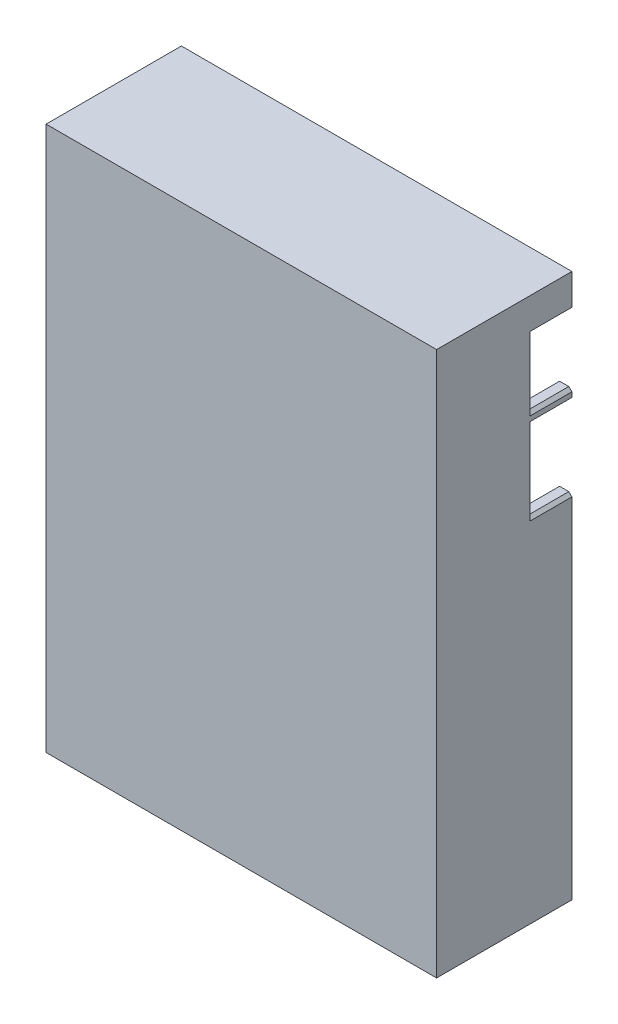
SolidWorks part; units mm, degrees
ref_plane "Front Plane" through (0, 0, 0) normal (0, 0, 1) x (1, 0, 0)
ref_plane "Top Plane" through (0, 0, 0) normal (0, 1, 0) x (1, 0, 0)
ref_plane "Right Plane" through (0, 0, 0) normal (1, 0, 0) x (0, 0, -1)
ref_plane "Plane1" through (0, 0, 2) normal (0, 0, 1) x (1, 0, 0)
sketch "Sketch2" plane through (0, 0, 2) normal (0, 0, 1) x (1, 0, 0)
  line L0 (-36.8212, -25.2032) -> (-36.8212, 57.2968) construction
  line L1 (-39.8212, 60.2968) -> (23.6788, 60.2968)
  line L2 (-39.8212, 60.2968) -> (-39.8212, -28.2032)
  line L3 (-39.8212, -28.2032) -> (23.6788, -28.2032)
  line L4 (23.6788, 60.2968) -> (23.6788, -28.2032)
  line L5 (-36.8212, 57.2968) -> (20.6788, 57.2968) construction
  line L6 (20.6788, 57.2968) -> (20.6788, -25.2032) construction
  line L7 (20.6788, -25.2032) -> (-36.8212, -25.2032) construction
  dimension "D1" = 3
  dimension "D2" = 3
  dimension "D3" = 3
  dimension "D4" = 3
extrude "Boss-Extrude1" add sketch "Sketch2" along normal blind 2
sketch "Sketch3" plane through (0, 0, 2) normal (0, 0, -1) x (-1, 0, 0)
  line L4 (39.8212, -28.2032) -> (39.8212, 60.2968)
  line L5 (39.8212, 60.2968) -> (-23.6788, 60.2968)
  line L6 (-23.6788, 60.2968) -> (-23.6788, -28.2032)
  line L7 (-23.6788, -28.2032) -> (39.8212, -28.2032)
  line L8 (39.8212, -28.2032) -> (39.8212, 60.2968)
  line L9 (39.8212, 60.2968) -> (-23.6788, 60.2968)
  line L10 (-23.6788, 60.2968) -> (-23.6788, -28.2032)
  line L11 (-23.6788, -28.2032) -> (39.8212, -28.2032)
  line L16 (37.8212, -26.2032) -> (37.8212, 58.2968)
  line L17 (37.8212, 58.2968) -> (-21.6788, 58.2968)
  line L18 (-21.6788, 58.2968) -> (-21.6788, -26.2032)
  line L19 (-21.6788, -26.2032) -> (37.8212, -26.2032)
  line L20 (37.8212, -26.2032) -> (37.8212, 58.2968)
  line L21 (37.8212, 58.2968) -> (-21.6788, 58.2968)
  line L22 (-21.6788, 58.2968) -> (-21.6788, -26.2032)
  line L23 (-21.6788, -26.2032) -> (37.8212, -26.2032)
  dimension "D1" = 0
  dimension "D2" = 2
extrude "Boss-Extrude2" add sketch "Sketch3" along normal blind 20
sketch "Sketch4" plane through (23.6788, 0, 0) normal (1, 0, 0) x (0, 0, -1)
  line L0 (18, 60.2968) -> (18, -28.2032) construction
  line L1 (18, 29.0468) -> (11.65, 29.0468)
  line L2 (18, 29.0468) -> (18, 42.0468)
  line L3 (18, 42.0468) -> (11.65, 42.0468)
  line L4 (11.65, 29.0468) -> (11.65, 42.0468)
  line L5 (11.65, -25.2032) -> (11.65, 57.2968) construction
  line L7 (18, 43.8468) -> (11.65, 43.8468)
  line L8 (18, 43.8468) -> (18, 54.7468)
  line L9 (18, 54.7468) -> (11.65, 54.7468)
  line L10 (11.65, 43.8468) -> (11.65, 54.7468)
  line L11 (16.95, 47.7968) -> (16.95, 50.7968) construction
  line L12 (16.95, 32.7968) -> (16.95, 38.2968) construction
  point P16 (16.95, 49.2968)
  point P17 (11.65, 49.2968)
  point P18 (16.95, 35.5468)
  point P19 (11.65, 35.5468)
  dimension "D1" = 10.9
  dimension "D2" = 13
extrude "Cut-Extrude1" cut sketch "Sketch4" against normal up to surface (2 mm away) up to face at (21.6788, 16.0468, -8)
chamfer "Chamfer1" distance 0.5 angle 45 6 edges at (23.6788, 54.7468, -14.825) (23.6788, 49.2968, -11.65) (23.6788, 43.8468, -14.825) (23.6788, 42.0468, -14.825) (23.6788, 35.5468, -11.65) (23.6788, 29.0468, -14.825)
sketch "Sketch5" plane through (-39.8212, 0, 0) normal (-1, 0, 0) x (0, 0, 1)
  line L0 (-18, -28.2032) -> (-18, 60.2968) construction
  line L1 (4, 60.2968) -> (-18, 60.2968) construction
  line L2 (-11.65, 57.2968) -> (-11.65, -25.2032) construction
  line L3 (-18, 34.207) -> (-11.65, 34.207)
  line L4 (-18, 34.207) -> (-18, 9.207)
  line L5 (-18, 9.207) -> (-11.65, 9.207)
  line L6 (-11.65, 34.207) -> (-11.65, 9.207)
  circle A0 centre (-12.432, 40.6543) radius 0.75
  point P12 (-11.65, 33.6258)
  point P13 (-18, 7.3997)
  point P14 (-18, 3.9836)
  point P15 (-18, 9.207)
  dimension "D1" = 1.5
  dimension "D2" = 5.568
  dimension "D3" = 19.6425
  dimension "D4" = 25
extrude "Cut-Extrude3" cut sketch "Sketch5" against normal up to surface (2 mm away) up to face at (-37.8212, 16.0468, -8)
fillet "Fillet1" radius 6 2 edges at (-38.8212, 9.207, -18) (-38.8212, 34.207, -18)
